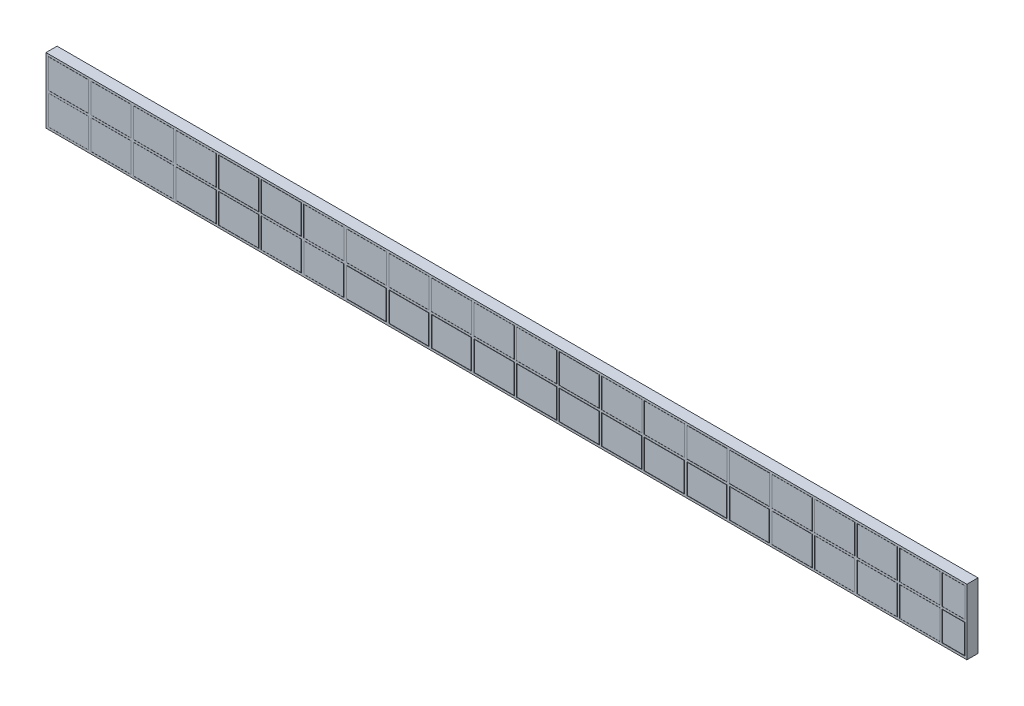
SolidWorks part; units mm, degrees
ref_plane "Alzado" through (0, 0, 0) normal (0, 0, 1) x (1, 0, 0)
ref_plane "Planta" through (0, 0, 0) normal (0, 1, 0) x (1, 0, 0)
ref_plane "Vista lateral" through (0, 0, 0) normal (1, 0, 0) x (0, 0, -1)
sketch "Croquis1" plane through (0, 0, 0) normal (0, 0, 1) x (1, 0, 0)
  line L1 (-9140, 650) -> (9140, 650)
  line L2 (-9140, 650) -> (-9140, -650)
  line L3 (-9140, -650) -> (9140, -650)
  line L4 (9140, 650) -> (9140, -650)
  line L5 (-9140, 650) -> (9140, -650) construction
  line L6 (-9140, -650) -> (9140, 650) construction
  point P0 (0, 0)
  dimension "D1" = 18280
  dimension "D2" = 1300
extrude "Saliente-Extruir1" add sketch "Croquis1" along normal blind 220
sketch "Croquis2" plane through (0, 0, 220) normal (0, 0, 1) x (1, 0, 0)
  line L0 (-9140, -650) -> (9140, -650) construction
  line L1 (-9095, -605) -> (-8295, -605)
  line L2 (-9095, -605) -> (-9095, -22.5)
  line L3 (-9095, -22.5) -> (-8295, -22.5)
  line L4 (-8295, -605) -> (-8295, -22.5)
  line L5 (-9095, -605) -> (-8295, -22.5) construction
  line L6 (-9095, -22.5) -> (-8295, -605) construction
  line L7 (-9095, 22.5) -> (-8295, 22.5)
  line L8 (-9095, 22.5) -> (-9095, 605)
  line L9 (-9095, 605) -> (-8295, 605)
  line L10 (-8295, 22.5) -> (-8295, 605)
  line L11 (-9095, 22.5) -> (-8295, 605) construction
  line L12 (-9095, 605) -> (-8295, 22.5) construction
  line L13 (-9140, 650) -> (-9140, -650) construction
  line L14 (9140, 650) -> (-9140, 650) construction
  line L16 (-7450, 22.5) -> (-8250, 22.5)
  line L17 (-7450, 22.5) -> (-7450, 605)
  line L18 (-7450, 605) -> (-8250, 605)
  line L19 (-8250, 22.5) -> (-8250, 605)
  line L20 (-7450, 22.5) -> (-8250, 605) construction
  line L21 (-7450, 605) -> (-8250, 22.5) construction
  line L22 (-7450, -605) -> (-8250, -605)
  line L23 (-7450, -605) -> (-7450, -22.5)
  line L24 (-7450, -22.5) -> (-8250, -22.5)
  line L25 (-8250, -605) -> (-8250, -22.5)
  line L26 (-7450, -605) -> (-8250, -22.5) construction
  line L27 (-7450, -22.5) -> (-8250, -605) construction
  line L28 (-6605, 22.5) -> (-7405, 22.5)
  line L29 (-6605, 22.5) -> (-6605, 605)
  line L30 (-6605, 605) -> (-7405, 605)
  line L31 (-7405, 22.5) -> (-7405, 605)
  line L32 (-6605, 22.5) -> (-7405, 605) construction
  line L33 (-6605, 605) -> (-7405, 22.5) construction
  line L34 (-5760, 22.5) -> (-6560, 22.5)
  line L35 (-5760, 22.5) -> (-5760, 605)
  line L36 (-5760, 605) -> (-6560, 605)
  line L37 (-6560, 22.5) -> (-6560, 605)
  line L38 (-5760, 22.5) -> (-6560, 605) construction
  line L39 (-5760, 605) -> (-6560, 22.5) construction
  line L40 (-4915, 22.5) -> (-5715, 22.5)
  line L41 (-4915, 22.5) -> (-4915, 605)
  line L42 (-4915, 605) -> (-5715, 605)
  line L43 (-5715, 22.5) -> (-5715, 605)
  line L44 (-4915, 22.5) -> (-5715, 605) construction
  line L45 (-4915, 605) -> (-5715, 22.5) construction
  line L46 (-4070, 22.5) -> (-4870, 22.5)
  line L47 (-4070, 22.5) -> (-4070, 605)
  line L48 (-4070, 605) -> (-4870, 605)
  line L49 (-4870, 22.5) -> (-4870, 605)
  line L50 (-4070, 22.5) -> (-4870, 605) construction
  line L51 (-4070, 605) -> (-4870, 22.5) construction
  line L52 (-3225, 22.5) -> (-4025, 22.5)
  line L53 (-3225, 22.5) -> (-3225, 605)
  line L54 (-3225, 605) -> (-4025, 605)
  line L55 (-4025, 22.5) -> (-4025, 605)
  line L56 (-3225, 22.5) -> (-4025, 605) construction
  line L57 (-3225, 605) -> (-4025, 22.5) construction
  line L58 (-2380, 22.5) -> (-3180, 22.5)
  line L59 (-2380, 22.5) -> (-2380, 605)
  line L60 (-2380, 605) -> (-3180, 605)
  line L61 (-3180, 22.5) -> (-3180, 605)
  line L62 (-2380, 22.5) -> (-3180, 605) construction
  line L63 (-2380, 605) -> (-3180, 22.5) construction
  line L64 (-1535, 22.5) -> (-2335, 22.5)
  line L65 (-1535, 22.5) -> (-1535, 605)
  line L66 (-1535, 605) -> (-2335, 605)
  line L67 (-2335, 22.5) -> (-2335, 605)
  line L68 (-1535, 22.5) -> (-2335, 605) construction
  line L69 (-1535, 605) -> (-2335, 22.5) construction
  line L70 (-690, 22.5) -> (-1490, 22.5)
  line L71 (-690, 22.5) -> (-690, 605)
  line L72 (-690, 605) -> (-1490, 605)
  line L73 (-1490, 22.5) -> (-1490, 605)
  line L74 (-690, 22.5) -> (-1490, 605) construction
  line L75 (-690, 605) -> (-1490, 22.5) construction
  line L76 (155, 22.5) -> (-645, 22.5)
  line L77 (155, 22.5) -> (155, 605)
  line L78 (155, 605) -> (-645, 605)
  line L79 (-645, 22.5) -> (-645, 605)
  line L80 (155, 22.5) -> (-645, 605) construction
  line L81 (155, 605) -> (-645, 22.5) construction
  line L82 (1000, 22.5) -> (200, 22.5)
  line L83 (1000, 22.5) -> (1000, 605)
  line L84 (1000, 605) -> (200, 605)
  line L85 (200, 22.5) -> (200, 605)
  line L86 (1000, 22.5) -> (200, 605) construction
  line L87 (1000, 605) -> (200, 22.5) construction
  line L88 (1845, 22.5) -> (1045, 22.5)
  line L89 (1845, 22.5) -> (1845, 605)
  line L90 (1845, 605) -> (1045, 605)
  line L91 (1045, 22.5) -> (1045, 605)
  line L92 (1845, 22.5) -> (1045, 605) construction
  line L93 (1845, 605) -> (1045, 22.5) construction
  line L94 (2690, 22.5) -> (1890, 22.5)
  line L95 (2690, 22.5) -> (2690, 605)
  line L96 (2690, 605) -> (1890, 605)
  line L97 (1890, 22.5) -> (1890, 605)
  line L98 (2690, 22.5) -> (1890, 605) construction
  line L99 (2690, 605) -> (1890, 22.5) construction
  line L100 (2735, 22.5) -> (3535, 22.5)
  line L101 (2735, 22.5) -> (2735, 605)
  line L102 (2735, 605) -> (3535, 605)
  line L103 (3535, 22.5) -> (3535, 605)
  line L104 (2735, 22.5) -> (3535, 605) construction
  line L105 (2735, 605) -> (3535, 22.5) construction
  line L106 (4380, 22.5) -> (3580, 22.5)
  line L107 (4380, 22.5) -> (4380, 605)
  line L108 (4380, 605) -> (3580, 605)
  line L109 (3580, 22.5) -> (3580, 605)
  line L110 (4380, 22.5) -> (3580, 605) construction
  line L111 (4380, 605) -> (3580, 22.5) construction
  line L112 (5225, 22.5) -> (4425, 22.5)
  line L113 (5225, 22.5) -> (5225, 605)
  line L114 (5225, 605) -> (4425, 605)
  line L115 (4425, 22.5) -> (4425, 605)
  line L116 (5225, 22.5) -> (4425, 605) construction
  line L117 (5225, 605) -> (4425, 22.5) construction
  line L118 (6070, 22.5) -> (5270, 22.5)
  line L119 (6070, 22.5) -> (6070, 605)
  line L120 (6070, 605) -> (5270, 605)
  line L121 (5270, 22.5) -> (5270, 605)
  line L122 (6070, 22.5) -> (5270, 605) construction
  line L123 (6070, 605) -> (5270, 22.5) construction
  line L124 (6915, 22.5) -> (6115, 22.5)
  line L125 (6915, 22.5) -> (6915, 605)
  line L126 (6915, 605) -> (6115, 605)
  line L127 (6115, 22.5) -> (6115, 605)
  line L128 (6915, 22.5) -> (6115, 605) construction
  line L129 (6915, 605) -> (6115, 22.5) construction
  line L130 (7760, 22.5) -> (6960, 22.5)
  line L131 (7760, 22.5) -> (7760, 605)
  line L132 (7760, 605) -> (6960, 605)
  line L133 (6960, 22.5) -> (6960, 605)
  line L134 (7760, 22.5) -> (6960, 605) construction
  line L135 (7760, 605) -> (6960, 22.5) construction
  line L136 (8605, 22.5) -> (7805, 22.5)
  line L137 (8605, 22.5) -> (8605, 605)
  line L138 (8605, 605) -> (7805, 605)
  line L139 (7805, 22.5) -> (7805, 605)
  line L140 (8605, 22.5) -> (7805, 605) construction
  line L141 (8605, 605) -> (7805, 22.5) construction
  line L142 (9100, 22.5) -> (8650, 22.5)
  line L143 (9100, 22.5) -> (9100, 605)
  line L144 (9100, 605) -> (8650, 605)
  line L145 (8650, 22.5) -> (8650, 605)
  line L146 (9100, 22.5) -> (8650, 605) construction
  line L147 (9100, 605) -> (8650, 22.5) construction
  line L148 (8651.9482, 602.4781) -> (9098.0518, 602.4781)
  line L149 (8651.9482, 602.4781) -> (8651.9482, 25.0219)
  line L150 (8651.9482, 25.0219) -> (9098.0518, 25.0219)
  line L151 (9098.0518, 602.4781) -> (9098.0518, 25.0219)
  line L152 (8651.9482, 602.4781) -> (9098.0518, 25.0219) construction
  line L153 (8651.9482, 25.0219) -> (9098.0518, 602.4781) construction
  line L154 (7808.4635, 602.4781) -> (8601.5365, 602.4781)
  line L155 (7808.4635, 602.4781) -> (7808.4635, 25.0219)
  line L156 (7808.4635, 25.0219) -> (8601.5365, 25.0219)
  line L157 (8601.5365, 602.4781) -> (8601.5365, 25.0219)
  line L158 (7808.4635, 602.4781) -> (8601.5365, 25.0219) construction
  line L159 (7808.4635, 25.0219) -> (8601.5365, 602.4781) construction
  line L160 (6963.4635, 602.4781) -> (7756.5365, 602.4781)
  line L161 (6963.4635, 602.4781) -> (6963.4635, 25.0219)
  line L162 (6963.4635, 25.0219) -> (7756.5365, 25.0219)
  line L163 (7756.5365, 602.4781) -> (7756.5365, 25.0219)
  line L164 (6963.4635, 602.4781) -> (7756.5365, 25.0219) construction
  line L165 (6963.4635, 25.0219) -> (7756.5365, 602.4781) construction
  line L166 (6118.4635, 602.4781) -> (6911.5365, 602.4781)
  line L167 (6118.4635, 602.4781) -> (6118.4635, 25.0219)
  line L168 (6118.4635, 25.0219) -> (6911.5365, 25.0219)
  line L169 (6911.5365, 602.4781) -> (6911.5365, 25.0219)
  line L170 (6118.4635, 602.4781) -> (6911.5365, 25.0219) construction
  line L171 (6118.4635, 25.0219) -> (6911.5365, 602.4781) construction
  line L172 (5273.4635, 602.4781) -> (6066.5365, 602.4781)
  line L173 (5273.4635, 602.4781) -> (5273.4635, 25.0219)
  line L174 (5273.4635, 25.0219) -> (6066.5365, 25.0219)
  line L175 (6066.5365, 602.4781) -> (6066.5365, 25.0219)
  line L176 (5273.4635, 602.4781) -> (6066.5365, 25.0219) construction
  line L177 (5273.4635, 25.0219) -> (6066.5365, 602.4781) construction
  line L178 (4430.1821, 601.2268) -> (5219.8179, 601.2268)
  line L179 (4430.1821, 601.2268) -> (4430.1821, 26.2732)
  line L180 (4430.1821, 26.2732) -> (5219.8179, 26.2732)
  line L181 (5219.8179, 601.2268) -> (5219.8179, 26.2732)
  line L182 (4430.1821, 601.2268) -> (5219.8179, 26.2732) construction
  line L183 (4430.1821, 26.2732) -> (5219.8179, 601.2268) construction
  line L184 (3585.1821, 601.2268) -> (4374.8179, 601.2268)
  line L185 (3585.1821, 601.2268) -> (3585.1821, 26.2732)
  line L186 (3585.1821, 26.2732) -> (4374.8179, 26.2732)
  line L187 (4374.8179, 601.2268) -> (4374.8179, 26.2732)
  line L188 (3585.1821, 601.2268) -> (4374.8179, 26.2732) construction
  line L189 (3585.1821, 26.2732) -> (4374.8179, 601.2268) construction
  line L190 (2738.4635, 602.4781) -> (3531.5365, 602.4781)
  line L191 (2738.4635, 602.4781) -> (2738.4635, 25.0219)
  line L192 (2738.4635, 25.0219) -> (3531.5365, 25.0219)
  line L193 (3531.5365, 602.4781) -> (3531.5365, 25.0219)
  line L194 (2738.4635, 602.4781) -> (3531.5365, 25.0219) construction
  line L195 (2738.4635, 25.0219) -> (3531.5365, 602.4781) construction
  line L196 (1893.4635, 602.4781) -> (2686.5365, 602.4781)
  line L197 (1893.4635, 602.4781) -> (1893.4635, 25.0219)
  line L198 (1893.4635, 25.0219) -> (2686.5365, 25.0219)
  line L199 (2686.5365, 602.4781) -> (2686.5365, 25.0219)
  line L200 (1893.4635, 602.4781) -> (2686.5365, 25.0219) construction
  line L201 (1893.4635, 25.0219) -> (2686.5365, 602.4781) construction
  line L202 (1050.1821, 601.2268) -> (1839.8179, 601.2268)
  line L203 (1050.1821, 601.2268) -> (1050.1821, 26.2732)
  line L204 (1050.1821, 26.2732) -> (1839.8179, 26.2732)
  line L205 (1839.8179, 601.2268) -> (1839.8179, 26.2732)
  line L206 (1050.1821, 601.2268) -> (1839.8179, 26.2732) construction
  line L207 (1050.1821, 26.2732) -> (1839.8179, 601.2268) construction
  line L208 (203.4635, 602.4781) -> (996.5365, 602.4781)
  line L209 (203.4635, 602.4781) -> (203.4635, 25.0219)
  line L210 (203.4635, 25.0219) -> (996.5365, 25.0219)
  line L211 (996.5365, 602.4781) -> (996.5365, 25.0219)
  line L212 (203.4635, 602.4781) -> (996.5365, 25.0219) construction
  line L213 (203.4635, 25.0219) -> (996.5365, 602.4781) construction
  line L214 (-641.5365, 602.4781) -> (151.5365, 602.4781)
  line L215 (-641.5365, 602.4781) -> (-641.5365, 25.0219)
  line L216 (-641.5365, 25.0219) -> (151.5365, 25.0219)
  line L217 (151.5365, 602.4781) -> (151.5365, 25.0219)
  line L218 (-641.5365, 602.4781) -> (151.5365, 25.0219) construction
  line L219 (-641.5365, 25.0219) -> (151.5365, 602.4781) construction
  line L220 (-1486.5365, 602.4781) -> (-693.4635, 602.4781)
  line L221 (-1486.5365, 602.4781) -> (-1486.5365, 25.0219)
  line L222 (-1486.5365, 25.0219) -> (-693.4635, 25.0219)
  line L223 (-693.4635, 602.4781) -> (-693.4635, 25.0219)
  line L224 (-1486.5365, 602.4781) -> (-693.4635, 25.0219) construction
  line L225 (-1486.5365, 25.0219) -> (-693.4635, 602.4781) construction
  line L226 (-2331.5365, 602.4781) -> (-1538.4635, 602.4781)
  line L227 (-2331.5365, 602.4781) -> (-2331.5365, 25.0219)
  line L228 (-2331.5365, 25.0219) -> (-1538.4635, 25.0219)
  line L229 (-1538.4635, 602.4781) -> (-1538.4635, 25.0219)
  line L230 (-2331.5365, 602.4781) -> (-1538.4635, 25.0219) construction
  line L231 (-2331.5365, 25.0219) -> (-1538.4635, 602.4781) construction
  line L232 (-3176.5365, 602.4781) -> (-2383.4635, 602.4781)
  line L233 (-3176.5365, 602.4781) -> (-3176.5365, 25.0219)
  line L234 (-3176.5365, 25.0219) -> (-2383.4635, 25.0219)
  line L235 (-2383.4635, 602.4781) -> (-2383.4635, 25.0219)
  line L236 (-3176.5365, 602.4781) -> (-2383.4635, 25.0219) construction
  line L237 (-3176.5365, 25.0219) -> (-2383.4635, 602.4781) construction
  line L238 (-4021.5365, 602.4781) -> (-3228.4635, 602.4781)
  line L239 (-4021.5365, 602.4781) -> (-4021.5365, 25.0219)
  line L240 (-4021.5365, 25.0219) -> (-3228.4635, 25.0219)
  line L241 (-3228.4635, 602.4781) -> (-3228.4635, 25.0219)
  line L242 (-4021.5365, 602.4781) -> (-3228.4635, 25.0219) construction
  line L243 (-4021.5365, 25.0219) -> (-3228.4635, 602.4781) construction
  line L244 (-4864.8179, 601.2268) -> (-4075.1821, 601.2268)
  line L245 (-4864.8179, 601.2268) -> (-4864.8179, 26.2732)
  line L246 (-4864.8179, 26.2732) -> (-4075.1821, 26.2732)
  line L247 (-4075.1821, 601.2268) -> (-4075.1821, 26.2732)
  line L248 (-4864.8179, 601.2268) -> (-4075.1821, 26.2732) construction
  line L249 (-4864.8179, 26.2732) -> (-4075.1821, 601.2268) construction
  line L250 (-5709.8179, 601.2268) -> (-4920.1821, 601.2268)
  line L251 (-5709.8179, 601.2268) -> (-5709.8179, 26.2732)
  line L252 (-5709.8179, 26.2732) -> (-4920.1821, 26.2732)
  line L253 (-4920.1821, 601.2268) -> (-4920.1821, 26.2732)
  line L254 (-5709.8179, 601.2268) -> (-4920.1821, 26.2732) construction
  line L255 (-5709.8179, 26.2732) -> (-4920.1821, 601.2268) construction
  line L256 (-6556.5365, 602.4781) -> (-5763.4635, 602.4781)
  line L257 (-6556.5365, 602.4781) -> (-6556.5365, 25.0219)
  line L258 (-6556.5365, 25.0219) -> (-5763.4635, 25.0219)
  line L259 (-5763.4635, 602.4781) -> (-5763.4635, 25.0219)
  line L260 (-6556.5365, 602.4781) -> (-5763.4635, 25.0219) construction
  line L261 (-6556.5365, 25.0219) -> (-5763.4635, 602.4781) construction
  line L262 (-7401.5365, 602.4781) -> (-6608.4635, 602.4781)
  line L263 (-7401.5365, 602.4781) -> (-7401.5365, 25.0219)
  line L264 (-7401.5365, 25.0219) -> (-6608.4635, 25.0219)
  line L265 (-6608.4635, 602.4781) -> (-6608.4635, 25.0219)
  line L266 (-7401.5365, 602.4781) -> (-6608.4635, 25.0219) construction
  line L267 (-7401.5365, 25.0219) -> (-6608.4635, 602.4781) construction
  line L268 (-8246.5365, 602.4781) -> (-7453.4635, 602.4781)
  line L269 (-8246.5365, 602.4781) -> (-8246.5365, 25.0219)
  line L270 (-8246.5365, 25.0219) -> (-7453.4635, 25.0219)
  line L271 (-7453.4635, 602.4781) -> (-7453.4635, 25.0219)
  line L272 (-8246.5365, 602.4781) -> (-7453.4635, 25.0219) construction
  line L273 (-8246.5365, 25.0219) -> (-7453.4635, 602.4781) construction
  line L274 (-9091.5365, 602.4781) -> (-8298.4635, 602.4781)
  line L275 (-9091.5365, 602.4781) -> (-9091.5365, 25.0219)
  line L276 (-9091.5365, 25.0219) -> (-8298.4635, 25.0219)
  line L277 (-8298.4635, 602.4781) -> (-8298.4635, 25.0219)
  line L278 (-9091.5365, 602.4781) -> (-8298.4635, 25.0219) construction
  line L279 (-9091.5365, 25.0219) -> (-8298.4635, 602.4781) construction
  line L280 (-9093.0098, -23.9491) -> (-8296.9902, -23.9491)
  line L281 (-9093.0098, -23.9491) -> (-9093.0098, -603.5509)
  line L282 (-9093.0098, -603.5509) -> (-8296.9902, -603.5509)
  line L283 (-8296.9902, -23.9491) -> (-8296.9902, -603.5509)
  line L284 (-9093.0098, -23.9491) -> (-8296.9902, -603.5509) construction
  line L285 (-9093.0098, -603.5509) -> (-8296.9902, -23.9491) construction
  line L286 (-8246.5365, -25.0219) -> (-7453.4635, -25.0219)
  line L287 (-8246.5365, -25.0219) -> (-8246.5365, -602.4781)
  line L288 (-8246.5365, -602.4781) -> (-7453.4635, -602.4781)
  line L289 (-7453.4635, -25.0219) -> (-7453.4635, -602.4781)
  line L290 (-8246.5365, -25.0219) -> (-7453.4635, -602.4781) construction
  line L291 (-8246.5365, -602.4781) -> (-7453.4635, -25.0219) construction
  line L292 (-6605, -605) -> (-7405, -605)
  line L293 (-6605, -605) -> (-6605, -22.5)
  line L294 (-6605, -22.5) -> (-7405, -22.5)
  line L295 (-7405, -605) -> (-7405, -22.5)
  line L296 (-6605, -605) -> (-7405, -22.5) construction
  line L297 (-6605, -22.5) -> (-7405, -605) construction
  line L298 (-5760, -605) -> (-6560, -605)
  line L299 (-5760, -605) -> (-5760, -22.5)
  line L300 (-5760, -22.5) -> (-6560, -22.5)
  line L301 (-6560, -605) -> (-6560, -22.5)
  line L302 (-5760, -605) -> (-6560, -22.5) construction
  line L303 (-5760, -22.5) -> (-6560, -605) construction
  line L304 (-5715, -22.5) -> (-4915, -22.5)
  line L305 (-5715, -22.5) -> (-5715, -605)
  line L306 (-5715, -605) -> (-4915, -605)
  line L307 (-4915, -22.5) -> (-4915, -605)
  line L308 (-5715, -22.5) -> (-4915, -605) construction
  line L309 (-5715, -605) -> (-4915, -22.5) construction
  line L310 (-4870, -22.5) -> (-4070, -22.5)
  line L311 (-4870, -22.5) -> (-4870, -605)
  line L312 (-4870, -605) -> (-4070, -605)
  line L313 (-4070, -22.5) -> (-4070, -605)
  line L314 (-4870, -22.5) -> (-4070, -605) construction
  line L315 (-4870, -605) -> (-4070, -22.5) construction
  line L316 (-4021.5365, -22.5) -> (-3228.4635, -22.5)
  line L317 (-4021.5365, -22.5) -> (-4021.5365, -605)
  line L318 (-4021.5365, -605) -> (-3228.4635, -605)
  line L319 (-3228.4635, -22.5) -> (-3228.4635, -605)
  line L320 (-4021.5365, -22.5) -> (-3228.4635, -605) construction
  line L321 (-4021.5365, -605) -> (-3228.4635, -22.5) construction
  line L322 (-3180, -22.5) -> (-2380, -22.5)
  line L323 (-3180, -22.5) -> (-3180, -605)
  line L324 (-3180, -605) -> (-2380, -605)
  line L325 (-2380, -22.5) -> (-2380, -605)
  line L326 (-3180, -22.5) -> (-2380, -605) construction
  line L327 (-3180, -605) -> (-2380, -22.5) construction
  line L328 (-2335, -22.5) -> (-1535, -22.5)
  line L329 (-2335, -22.5) -> (-2335, -605)
  line L330 (-2335, -605) -> (-1535, -605)
  line L331 (-1535, -22.5) -> (-1535, -605)
  line L332 (-2335, -22.5) -> (-1535, -605) construction
  line L333 (-2335, -605) -> (-1535, -22.5) construction
  line L334 (-1486.5365, -22.5) -> (-693.4635, -22.5)
  line L335 (-1486.5365, -22.5) -> (-1486.5365, -605)
  line L336 (-1486.5365, -605) -> (-693.4635, -605)
  line L337 (-693.4635, -22.5) -> (-693.4635, -605)
  line L338 (-1486.5365, -22.5) -> (-693.4635, -605) construction
  line L339 (-1486.5365, -605) -> (-693.4635, -22.5) construction
  line L340 (-645, -22.5) -> (155, -22.5)
  line L341 (-645, -22.5) -> (-645, -605)
  line L342 (-645, -605) -> (155, -605)
  line L343 (155, -22.5) -> (155, -605)
  line L344 (-645, -22.5) -> (155, -605) construction
  line L345 (-645, -605) -> (155, -22.5) construction
  line L346 (200, -22.5) -> (1000, -22.5)
  line L347 (200, -22.5) -> (200, -605)
  line L348 (200, -605) -> (1000, -605)
  line L349 (1000, -22.5) -> (1000, -605)
  line L350 (200, -22.5) -> (1000, -605) construction
  line L351 (200, -605) -> (1000, -22.5) construction
  line L352 (1045, -22.5) -> (1845, -22.5)
  line L353 (1045, -22.5) -> (1045, -605)
  line L354 (1045, -605) -> (1845, -605)
  line L355 (1845, -22.5) -> (1845, -605)
  line L356 (1045, -22.5) -> (1845, -605) construction
  line L357 (1045, -605) -> (1845, -22.5) construction
  line L358 (2690, -605) -> (1890, -605)
  line L359 (2690, -605) -> (2690, -22.5)
  line L360 (2690, -22.5) -> (1890, -22.5)
  line L361 (1890, -605) -> (1890, -22.5)
  line L362 (2690, -605) -> (1890, -22.5) construction
  line L363 (2690, -22.5) -> (1890, -605) construction
  line L364 (2735, -22.5) -> (3535, -22.5)
  line L365 (2735, -22.5) -> (2735, -605)
  line L366 (2735, -605) -> (3535, -605)
  line L367 (3535, -22.5) -> (3535, -605)
  line L368 (2735, -22.5) -> (3535, -605) construction
  line L369 (2735, -605) -> (3535, -22.5) construction
  line L370 (4380, -605) -> (3580, -605)
  line L371 (4380, -605) -> (4380, -22.5)
  line L372 (4380, -22.5) -> (3580, -22.5)
  line L373 (3580, -605) -> (3580, -22.5)
  line L374 (4380, -605) -> (3580, -22.5) construction
  line L375 (4380, -22.5) -> (3580, -605) construction
  line L376 (4430.1821, -22.5) -> (5219.8179, -22.5)
  line L377 (4430.1821, -22.5) -> (4430.1821, -605)
  line L378 (4430.1821, -605) -> (5219.8179, -605)
  line L379 (5219.8179, -22.5) -> (5219.8179, -605)
  line L380 (4430.1821, -22.5) -> (5219.8179, -605) construction
  line L381 (4430.1821, -605) -> (5219.8179, -22.5) construction
  line L382 (5270, -22.5) -> (6070, -22.5)
  line L383 (5270, -22.5) -> (5270, -605)
  line L384 (5270, -605) -> (6070, -605)
  line L385 (6070, -22.5) -> (6070, -605)
  line L386 (5270, -22.5) -> (6070, -605) construction
  line L387 (5270, -605) -> (6070, -22.5) construction
  line L388 (6118.4635, -22.5) -> (6911.5365, -22.5)
  line L389 (6118.4635, -22.5) -> (6118.4635, -605)
  line L390 (6118.4635, -605) -> (6911.5365, -605)
  line L391 (6911.5365, -22.5) -> (6911.5365, -605)
  line L392 (6118.4635, -22.5) -> (6911.5365, -605) construction
  line L393 (6118.4635, -605) -> (6911.5365, -22.5) construction
  line L394 (6960, -22.5) -> (7760, -22.5)
  line L395 (6960, -22.5) -> (6960, -605)
  line L396 (6960, -605) -> (7760, -605)
  line L397 (7760, -22.5) -> (7760, -605)
  line L398 (6960, -22.5) -> (7760, -605) construction
  line L399 (6960, -605) -> (7760, -22.5) construction
  line L400 (7805, -22.5) -> (8605, -22.5)
  line L401 (7805, -22.5) -> (7805, -605)
  line L402 (7805, -605) -> (8605, -605)
  line L403 (8605, -22.5) -> (8605, -605)
  line L404 (7805, -22.5) -> (8605, -605) construction
  line L405 (7805, -605) -> (8605, -22.5) construction
  line L406 (9100, -605) -> (8650, -605)
  line L407 (9100, -605) -> (9100, -22.5)
  line L408 (9100, -22.5) -> (8650, -22.5)
  line L409 (8650, -605) -> (8650, -22.5)
  line L410 (9100, -605) -> (8650, -22.5) construction
  line L411 (9100, -22.5) -> (8650, -605) construction
  line L412 (9095.0466, -28.9119) -> (8654.9534, -28.9119)
  line L413 (9095.0466, -28.9119) -> (9095.0466, -598.5881)
  line L414 (9095.0466, -598.5881) -> (8654.9534, -598.5881)
  line L415 (8654.9534, -28.9119) -> (8654.9534, -598.5881)
  line L416 (9095.0466, -28.9119) -> (8654.9534, -598.5881) construction
  line L417 (9095.0466, -598.5881) -> (8654.9534, -28.9119) construction
  line L418 (8601.5365, -25.0219) -> (7808.4635, -25.0219)
  line L419 (8601.5365, -25.0219) -> (8601.5365, -602.4781)
  line L420 (8601.5365, -602.4781) -> (7808.4635, -602.4781)
  line L421 (7808.4635, -25.0219) -> (7808.4635, -602.4781)
  line L422 (8601.5365, -25.0219) -> (7808.4635, -602.4781) construction
  line L423 (8601.5365, -602.4781) -> (7808.4635, -25.0219) construction
  line L424 (6963.4635, -25.0219) -> (7756.5365, -25.0219)
  line L425 (6963.4635, -25.0219) -> (6963.4635, -602.4781)
  line L426 (6963.4635, -602.4781) -> (7756.5365, -602.4781)
  line L427 (7756.5365, -25.0219) -> (7756.5365, -602.4781)
  line L428 (6963.4635, -25.0219) -> (7756.5365, -602.4781) construction
  line L429 (6963.4635, -602.4781) -> (7756.5365, -25.0219) construction
  line L430 (6121.897, -25.0219) -> (6908.103, -25.0219)
  line L431 (6121.897, -25.0219) -> (6121.897, -602.4781)
  line L432 (6121.897, -602.4781) -> (6908.103, -602.4781)
  line L433 (6908.103, -25.0219) -> (6908.103, -602.4781)
  line L434 (6121.897, -25.0219) -> (6908.103, -602.4781) construction
  line L435 (6121.897, -602.4781) -> (6908.103, -25.0219) construction
  line L436 (5275.5952, -26.574) -> (6064.4048, -26.574)
  line L437 (5275.5952, -26.574) -> (5275.5952, -600.926)
  line L438 (5275.5952, -600.926) -> (6064.4048, -600.926)
  line L439 (6064.4048, -26.574) -> (6064.4048, -600.926)
  line L440 (5275.5952, -26.574) -> (6064.4048, -600.926) construction
  line L441 (5275.5952, -600.926) -> (6064.4048, -26.574) construction
  line L442 (4435.7049, -26.574) -> (5214.2951, -26.574)
  line L443 (4435.7049, -26.574) -> (4435.7049, -600.926)
  line L444 (4435.7049, -600.926) -> (5214.2951, -600.926)
  line L445 (5214.2951, -26.574) -> (5214.2951, -600.926)
  line L446 (4435.7049, -26.574) -> (5214.2951, -600.926) construction
  line L447 (4435.7049, -600.926) -> (5214.2951, -26.574) construction
  line L448 (3588.806, -28.9119) -> (4371.194, -28.9119)
  line L449 (3588.806, -28.9119) -> (3588.806, -598.5881)
  line L450 (3588.806, -598.5881) -> (4371.194, -598.5881)
  line L451 (4371.194, -28.9119) -> (4371.194, -598.5881)
  line L452 (3588.806, -28.9119) -> (4371.194, -598.5881) construction
  line L453 (3588.806, -598.5881) -> (4371.194, -28.9119) construction
  line L454 (2743.806, -28.9119) -> (3526.194, -28.9119)
  line L455 (2743.806, -28.9119) -> (2743.806, -598.5881)
  line L456 (2743.806, -598.5881) -> (3526.194, -598.5881)
  line L457 (3526.194, -28.9119) -> (3526.194, -598.5881)
  line L458 (2743.806, -28.9119) -> (3526.194, -598.5881) construction
  line L459 (2743.806, -598.5881) -> (3526.194, -28.9119) construction
  line L460 (1898.806, -28.9119) -> (2681.194, -28.9119)
  line L461 (1898.806, -28.9119) -> (1898.806, -598.5881)
  line L462 (1898.806, -598.5881) -> (2681.194, -598.5881)
  line L463 (2681.194, -28.9119) -> (2681.194, -598.5881)
  line L464 (1898.806, -28.9119) -> (2681.194, -598.5881) construction
  line L465 (1898.806, -598.5881) -> (2681.194, -28.9119) construction
  line L466 (1053.806, -28.9119) -> (1836.194, -28.9119)
  line L467 (1053.806, -28.9119) -> (1053.806, -598.5881)
  line L468 (1053.806, -598.5881) -> (1836.194, -598.5881)
  line L469 (1836.194, -28.9119) -> (1836.194, -598.5881)
  line L470 (1053.806, -28.9119) -> (1836.194, -598.5881) construction
  line L471 (1053.806, -598.5881) -> (1836.194, -28.9119) construction
  line L472 (208.806, -28.9119) -> (991.194, -28.9119)
  line L473 (208.806, -28.9119) -> (208.806, -598.5881)
  line L474 (208.806, -598.5881) -> (991.194, -598.5881)
  line L475 (991.194, -28.9119) -> (991.194, -598.5881)
  line L476 (208.806, -28.9119) -> (991.194, -598.5881) construction
  line L477 (208.806, -598.5881) -> (991.194, -28.9119) construction
  line L478 (-636.194, -28.9119) -> (146.194, -28.9119)
  line L479 (-636.194, -28.9119) -> (-636.194, -598.5881)
  line L480 (-636.194, -598.5881) -> (146.194, -598.5881)
  line L481 (146.194, -28.9119) -> (146.194, -598.5881)
  line L482 (-636.194, -28.9119) -> (146.194, -598.5881) construction
  line L483 (-636.194, -598.5881) -> (146.194, -28.9119) construction
  line L484 (-1477.8067, -28.9119) -> (-702.1933, -28.9119)
  line L485 (-1477.8067, -28.9119) -> (-1477.8067, -598.5881)
  line L486 (-1477.8067, -598.5881) -> (-702.1933, -598.5881)
  line L487 (-702.1933, -28.9119) -> (-702.1933, -598.5881)
  line L488 (-1477.8067, -28.9119) -> (-702.1933, -598.5881) construction
  line L489 (-1477.8067, -598.5881) -> (-702.1933, -28.9119) construction
  line L490 (-2326.194, -28.9119) -> (-1543.806, -28.9119)
  line L491 (-2326.194, -28.9119) -> (-2326.194, -598.5881)
  line L492 (-2326.194, -598.5881) -> (-1543.806, -598.5881)
  line L493 (-1543.806, -28.9119) -> (-1543.806, -598.5881)
  line L494 (-2326.194, -28.9119) -> (-1543.806, -598.5881) construction
  line L495 (-2326.194, -598.5881) -> (-1543.806, -28.9119) construction
  line L496 (-3171.194, -28.9119) -> (-2388.806, -28.9119)
  line L497 (-3171.194, -28.9119) -> (-3171.194, -598.5881)
  line L498 (-3171.194, -598.5881) -> (-2388.806, -598.5881)
  line L499 (-2388.806, -28.9119) -> (-2388.806, -598.5881)
  line L500 (-3171.194, -28.9119) -> (-2388.806, -598.5881) construction
  line L501 (-3171.194, -598.5881) -> (-2388.806, -28.9119) construction
  line L502 (-4018.103, -25.0219) -> (-3231.897, -25.0219)
  line L503 (-4018.103, -25.0219) -> (-4018.103, -602.4781)
  line L504 (-4018.103, -602.4781) -> (-3231.897, -602.4781)
  line L505 (-3231.897, -25.0219) -> (-3231.897, -602.4781)
  line L506 (-4018.103, -25.0219) -> (-3231.897, -602.4781) construction
  line L507 (-4018.103, -602.4781) -> (-3231.897, -25.0219) construction
  line L508 (-4866.5365, -25.0219) -> (-4073.4635, -25.0219)
  line L509 (-4866.5365, -25.0219) -> (-4866.5365, -602.4781)
  line L510 (-4866.5365, -602.4781) -> (-4073.4635, -602.4781)
  line L511 (-4073.4635, -25.0219) -> (-4073.4635, -602.4781)
  line L512 (-4866.5365, -25.0219) -> (-4073.4635, -602.4781) construction
  line L513 (-4866.5365, -602.4781) -> (-4073.4635, -25.0219) construction
  line L514 (-5709.8179, -26.2732) -> (-4920.1821, -26.2732)
  line L515 (-5709.8179, -26.2732) -> (-5709.8179, -601.2268)
  line L516 (-5709.8179, -601.2268) -> (-4920.1821, -601.2268)
  line L517 (-4920.1821, -26.2732) -> (-4920.1821, -601.2268)
  line L518 (-5709.8179, -26.2732) -> (-4920.1821, -601.2268) construction
  line L519 (-5709.8179, -601.2268) -> (-4920.1821, -26.2732) construction
  line L520 (-6554.8179, -26.2732) -> (-5765.1821, -26.2732)
  line L521 (-6554.8179, -26.2732) -> (-6554.8179, -601.2268)
  line L522 (-6554.8179, -601.2268) -> (-5765.1821, -601.2268)
  line L523 (-5765.1821, -26.2732) -> (-5765.1821, -601.2268)
  line L524 (-6554.8179, -26.2732) -> (-5765.1821, -601.2268) construction
  line L525 (-6554.8179, -601.2268) -> (-5765.1821, -26.2732) construction
  line L526 (-7401.5365, -25.0219) -> (-6608.4635, -25.0219)
  line L527 (-7401.5365, -25.0219) -> (-7401.5365, -602.4781)
  line L528 (-7401.5365, -602.4781) -> (-6608.4635, -602.4781)
  line L529 (-6608.4635, -25.0219) -> (-6608.4635, -602.4781)
  line L530 (-7401.5365, -25.0219) -> (-6608.4635, -602.4781) construction
  line L531 (-7401.5365, -602.4781) -> (-6608.4635, -25.0219) construction
  point P0 (-8695, -313.75)
  point P5 (-8695, 313.75)
  point P16 (-7850, 313.75)
  point P21 (-7850, -313.75)
  point P26 (-7005, 313.75)
  point P31 (-6160, 313.75)
  point P36 (-5315, 313.75)
  point P41 (-4470, 313.75)
  point P46 (-3625, 313.75)
  point P51 (-2780, 313.75)
  point P56 (-1935, 313.75)
  point P61 (-1090, 313.75)
  point P66 (-245, 313.75)
  point P71 (600, 313.75)
  point P76 (1445, 313.75)
  point P81 (2290, 313.75)
  point P86 (3135, 313.75)
  point P91 (3980, 313.75)
  point P96 (4825, 313.75)
  point P101 (5670, 313.75)
  point P106 (6515, 313.75)
  point P111 (7360, 313.75)
  point P116 (8205, 313.75)
  point P121 (8875, 313.75)
  point P126 (8875, 313.75)
  point P131 (8205, 313.75)
  point P136 (7360, 313.75)
  point P141 (6515, 313.75)
  point P146 (5670, 313.75)
  point P151 (4825, 313.75)
  point P156 (3980, 313.75)
  point P161 (3135, 313.75)
  point P166 (2290, 313.75)
  point P171 (1445, 313.75)
  point P176 (600, 313.75)
  point P181 (-245, 313.75)
  point P186 (-1090, 313.75)
  point P191 (-1935, 313.75)
  point P196 (-2780, 313.75)
  point P201 (-3625, 313.75)
  point P206 (-4470, 313.75)
  point P211 (-5315, 313.75)
  point P216 (-6160, 313.75)
  point P221 (-7005, 313.75)
  point P226 (-7850, 313.75)
  point P231 (-8695, 313.75)
  point P236 (-8695, -313.75)
  point P241 (-7850, -313.75)
  point P246 (-7005, -313.75)
  point P251 (-6160, -313.75)
  point P256 (-5315, -313.75)
  point P261 (-4470, -313.75)
  point P266 (-3625, -313.75)
  point P271 (-2780, -313.75)
  point P276 (-1935, -313.75)
  point P281 (-1090, -313.75)
  point P286 (-245, -313.75)
  point P291 (600, -313.75)
  point P296 (1445, -313.75)
  point P301 (2290, -313.75)
  point P306 (3135, -313.75)
  point P311 (3980, -313.75)
  point P316 (4825, -313.75)
  point P321 (5670, -313.75)
  point P326 (6515, -313.75)
  point P331 (7360, -313.75)
  point P336 (8205, -313.75)
  point P341 (8875, -313.75)
  point P346 (8875, -313.75)
  point P351 (8205, -313.75)
  point P356 (7360, -313.75)
  point P361 (6515, -313.75)
  point P366 (5670, -313.75)
  point P371 (4825, -313.75)
  point P376 (3980, -313.75)
  point P381 (3135, -313.75)
  point P386 (2290, -313.75)
  point P391 (1445, -313.75)
  point P396 (600, -313.75)
  point P401 (-245, -313.75)
  point P406 (-1090, -313.75)
  point P411 (-1935, -313.75)
  point P416 (-2780, -313.75)
  point P421 (-3625, -313.75)
  point P426 (-4470, -313.75)
  point P431 (-5315, -313.75)
  point P436 (-6160, -313.75)
  point P441 (-7005, -313.75)
  dimension "D1" = 45
  dimension "D2" = 45
  dimension "D3" = 45
  dimension "D4" = 45
  dimension "D5" = 582.5
  dimension "D6" = 582.5
  dimension "D7" = 800
  dimension "D8" = 800
  dimension "D9" = 45
  dimension "D10" = 800
  dimension "D11" = 45
  dimension "D12" = 800
  dimension "D13" = 45
  dimension "D14" = 800
  dimension "D15" = 45
  dimension "D16" = 800
  dimension "D17" = 582.5
  dimension "D18" = 45
  dimension "D19" = 800
  dimension "D20" = 45
  dimension "D21" = 800
  dimension "D22" = 45
  dimension "D23" = 800
  dimension "D24" = 45
  dimension "D25" = 800
  dimension "D26" = 45
  dimension "D27" = 800
  dimension "D28" = 45
  dimension "D29" = 800
  dimension "D30" = 45
  dimension "D31" = 800
  dimension "D32" = 45
  dimension "D33" = 800
  dimension "D34" = 45
  dimension "D35" = 800
  dimension "D36" = 45
  dimension "D37" = 800
  dimension "D38" = 45
  dimension "D39" = 800
  dimension "D40" = 45
  dimension "D41" = 800
  dimension "D42" = 45
  dimension "D43" = 800
  dimension "D44" = 45
  dimension "D45" = 800
  dimension "D46" = 45
  dimension "D47" = 800
  dimension "D48" = 45
  dimension "D49" = 800
  dimension "D50" = 45
  dimension "D51" = 450
extrude "Cortar-Extruir1" cut sketch "Croquis2" against normal blind 220
